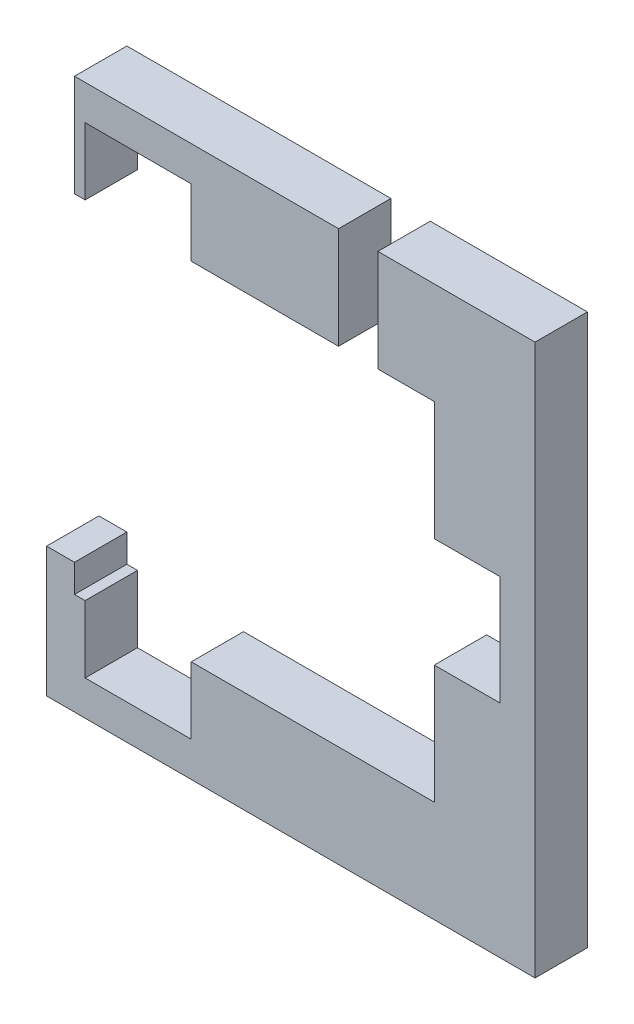
SolidWorks part; units mm, degrees
ref_plane "Front Plane" through (0, 0, 0) normal (0, 0, 1) x (1, 0, 0)
ref_plane "Top Plane" through (0, 0, 0) normal (0, 1, 0) x (1, 0, 0)
ref_plane "Right Plane" through (0, 0, 0) normal (1, 0, 0) x (0, 0, -1)
sketch "Sketch1" plane through (0, 0, 0) normal (0, 0, 1) x (1, 0, 0)
  line L0 (7547.3402, 3420.4566) -> (7547.3402, 3429.7276)
  line L1 (7544.8002, 3379.6134) -> (7544.8002, 3391.4244)
  line L2 (7548.3054, 3420.4566) -> (7548.3054, 3426.5526)
  line L3 (7557.9574, 3420.4566) -> (7557.9574, 3426.5526)
  line L4 (7547.3402, 3420.4566) -> (7548.3054, 3420.4566)
  line L5 (7557.9574, 3420.4566) -> (7571.3686, 3420.4566)
  line L6 (7574.95, 3420.4566) -> (7580.0808, 3420.4566)
  line L7 (7548.3054, 3426.5526) -> (7557.9574, 3426.5526)
  line L8 (7547.3402, 3429.7276) -> (7571.3686, 3429.7276)
  line L9 (7574.95, 3429.7276) -> (7589.2502, 3429.7276)
  line L10 (7580.0808, 3420.4566) -> (7580.0808, 3409.6489)
  line L11 (7580.0808, 3399.6921) -> (7580.0808, 3388.8844)
  line L12 (7571.3686, 3429.7276) -> (7571.3686, 3420.4566)
  line L13 (7574.95, 3429.7276) -> (7574.95, 3420.4566)
  line L14 (7586.0752, 3409.6489) -> (7586.0752, 3399.6921)
  line L15 (7589.2502, 3429.7276) -> (7589.2502, 3379.6134)
  line L16 (7580.0808, 3388.8844) -> (7557.9574, 3388.8844)
  line L17 (7548.3054, 3388.8844) -> (7547.3402, 3388.8844)
  line L18 (7580.0808, 3399.6921) -> (7586.0752, 3399.6921)
  line L19 (7580.0808, 3409.6489) -> (7586.0752, 3409.6489)
  line L20 (7548.3054, 3388.8844) -> (7548.3054, 3382.7884)
  line L21 (7557.9574, 3388.8844) -> (7557.9574, 3382.7884)
  line L22 (7548.3054, 3382.7884) -> (7557.9574, 3382.7884)
  line L23 (7544.8002, 3379.6134) -> (7589.2502, 3379.6134)
  line L24 (7547.3402, 3391.4244) -> (7544.8002, 3391.4244)
  line L25 (7547.3402, 3391.4244) -> (7547.3402, 3388.8844)
extrude "Boss-Extrude1" add sketch "Sketch1" along normal blind 4.7625
